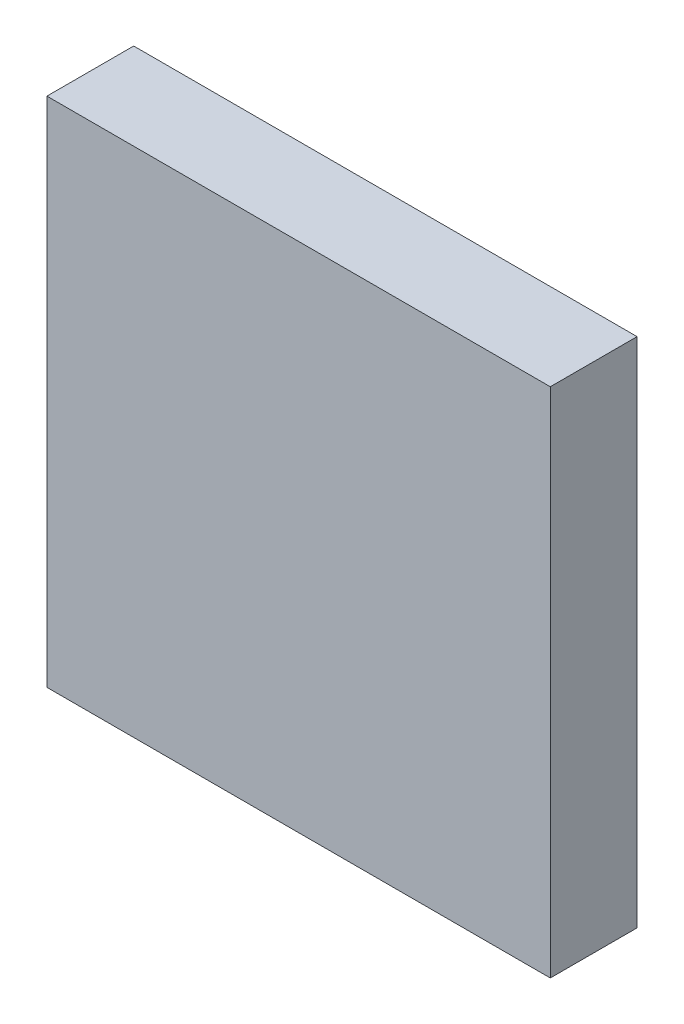
SolidWorks part; units mm, degrees
ref_plane "Plan de face" through (0, 0, 0) normal (0, 0, 1) x (1, 0, 0)
ref_plane "Plan de dessus" through (0, 0, 0) normal (0, 1, 0) x (1, 0, 0)
ref_plane "Plan de droite" through (0, 0, 0) normal (1, 0, 0) x (0, 0, -1)
sketch "Esquisse1" plane through (0, 0, 0) normal (0, 0, 1) x (1, 0, 0)
  line L1 (27.154, -40.3301) -> (-30.846, -40.3301)
  line L2 (27.154, -40.3301) -> (27.154, 18.6699)
  line L3 (27.154, 18.6699) -> (-30.846, 18.6699)
  line L4 (-30.846, -40.3301) -> (-30.846, 18.6699)
  dimension "D1" = 58
  dimension "D2" = 59
extrude "Boss.-Extru.1" add sketch "Esquisse1" along normal blind 10
